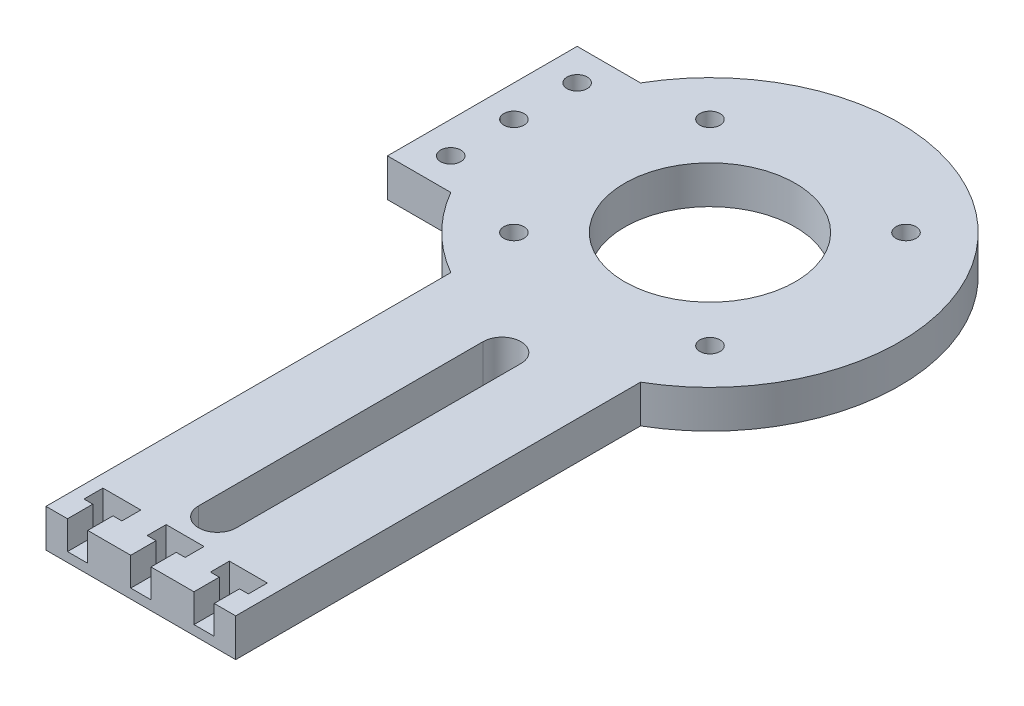
SolidWorks part; units mm, degrees
ref_plane "前视基准面" through (0, 0, 0) normal (0, 0, 1) x (1, 0, 0)
ref_plane "上视基准面" through (0, 0, 0) normal (0, 1, 0) x (1, 0, 0)
ref_plane "右视基准面" through (0, 0, 0) normal (1, 0, 0) x (0, 0, -1)
other "Configuration Table"
sketch "草图1" plane through (0, 0, 0) normal (0, 1, 0) x (1, 0, 0)
  line L0 (15, 80) -> (15, -49920) construction
  line L1 (0, 0) -> (30, 0)
  line L2 (0, 0) -> (0, 90)
  line L3 (0, 90) -> (30, 90)
  line L4 (30, 0) -> (30, 90)
  line L5 (15, 90) -> (50015, 90) construction
  line L6 (15, 12.1139) -> (15, 57.1139) construction
  line L7 (12, 12.1139) -> (12, 57.1139)
  line L8 (18, 12.1139) -> (18, 57.1139)
  line L9 (15, 90) -> (35370.3391, 35445.3391) construction
  line L10 (15, 90) -> (35370.3391, -35265.3391) construction
  circle A0 centre (15, 90) radius 30
  circle A1 centre (30.5, 105.5) radius 1.6
  circle A2 centre (-0.5, 105.5) radius 1.6
  circle A5 centre (15, 90) radius 13.5
  arc A6 (12, 12.1139) -> (18, 12.1139) centre (15, 12.1139) ccw
  arc A7 (18, 57.1139) -> (12, 57.1139) centre (15, 57.1139) ccw
  circle A8 centre (15, 90) radius 17.5 construction
  circle A13 centre (30.5, 74.5) radius 1.6
  circle A14 centre (-0.5, 74.5) radius 1.6
  point P22 (15, 34.6139)
  dimension "D3" = 60
  dimension "D4" = 15.5
  dimension "D5" = 15.5
  dimension "D6" = 3.2
  dimension "D7" = 27
  dimension "D9" = 35
  dimension "D1" = 30
  dimension "D2" = 90
  dimension "D8" = 6
  dimension "D13" = 45
extrude "凸台-拉伸1" add sketch "草图1" along normal blind 6
sketch "草图3" plane through (0, 6, 0) normal (0, 1, 0) x (1, 0, 0)
  line L0 (15, 90) -> (50015, 90) construction
  line L1 (15, 90) -> (15, -49910) construction
  line L8 (-11, 75) -> (-21, 105) construction
  line L9 (-11, 105) -> (-21, 75) construction
  line L10 (-21, 105) -> (-21, 75)
  line L11 (-11, 75) -> (-21, 75)
  line L12 (-11, 105) -> (-11, 75)
  line L13 (-11, 105) -> (-21, 105)
  circle A3 centre (-16, 80) radius 1.6
  circle A4 centre (-16, 90) radius 1.6
  circle A5 centre (-16, 100) radius 1.6
  point P26 (-16, 90)
  dimension "D1" = 3.2
  dimension "D2" = 3.2
  dimension "D3" = 3.2
extrude "凸台-拉伸2" add sketch "草图3" against normal blind 6
sketch "草图7" plane through (0, 0, 0) normal (0, -1, 0) x (1, 0, 0)
  line L0 (0, 0) -> (30, 0) construction
  line L1 (26.6, 0) -> (23.4, 0)
  line L2 (26.6, 0) -> (26.6, -4)
  line L3 (26.6, -4) -> (23.4, -4)
  line L4 (23.4, 0) -> (23.4, -4)
  line L5 (30, 0) -> (30, -64.0192) construction
  line L6 (16.6, -4) -> (13.4, -4)
  line L7 (16.6, 0) -> (16.6, -4)
  line L8 (13.4, 0) -> (13.4, -4)
  line L9 (16.6, 0) -> (13.4, 0)
  line L10 (6.6, -4) -> (3.4, -4)
  line L11 (6.6, 0) -> (6.6, -4)
  line L12 (3.4, 0) -> (3.4, -4)
  line L13 (6.6, 0) -> (3.4, 0)
  dimension "D1" = 3.2
  dimension "D2" = 3.4
  dimension "D3" = 4
  dimension "D4" = 3
extrude "切除-拉伸3" cut sketch "草图7" against normal blind 14.5
sketch "草图8" plane through (0, 0, 0) normal (0, -1, 0) x (1, 0, 0)
  line L0 (8, -4) -> (8, -7)
  line L1 (2, -4) -> (8, -4)
  line L2 (2, -4) -> (2, -7)
  line L3 (2, -7) -> (8, -7)
  line L9 (6.6, 0) -> (13.4, 0) construction
  line L10 (0, 0) -> (0, -64.0192) construction
  line L11 (12, -4) -> (18, -4)
  line L12 (12, -4) -> (12, -7)
  line L13 (18, -4) -> (18, -7)
  line L14 (12, -7) -> (18, -7)
  line L15 (22, -4) -> (28, -4)
  line L16 (22, -4) -> (22, -7)
  line L17 (28, -4) -> (28, -7)
  line L18 (22, -7) -> (28, -7)
  dimension "D1" = 6
  dimension "D2" = 3
  dimension "D3" = 4
  dimension "D4" = 2
extrude "切除-拉伸4" cut sketch "草图8" against normal blind 14.5
sketch "草图10" plane through (0, 0, 0) normal (0, -1, 0) x (1, 0, 0)
  line L0 (28, -4) -> (26.6, -4) construction
  line L1 (3.4, 0) -> (26.7176, 0)
  line L2 (3.4, 0) -> (3.4, -4)
  line L3 (3.4, -4) -> (26.7176, -4)
  line L4 (26.7176, 0) -> (26.7176, -4)
extrude "凸台-拉伸3" add sketch "草图10" against normal blind 1.5
sketch "草图11" plane through (0, 6, 0) normal (0, 1, 0) x (1, 0, 0)
  circle A0 centre (-16, 90) radius 1.6
extrude "切除-拉伸5" cut sketch "草图11" against normal blind 10
